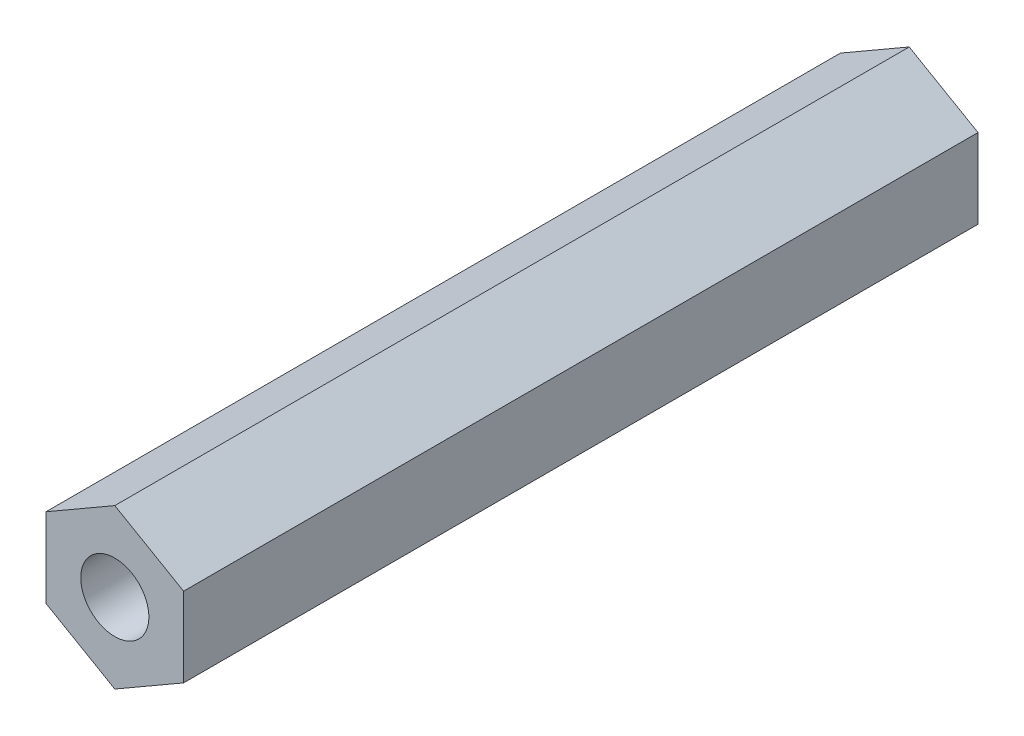
SolidWorks part; units mm, degrees
ref_plane "Front Plane" through (0, 0, 0) normal (0, 0, 1) x (1, 0, 0)
ref_plane "Top Plane" through (0, 0, 0) normal (0, 1, 0) x (1, 0, 0)
ref_plane "Right Plane" through (0, 0, 0) normal (1, 0, 0) x (0, 0, -1)
sketch "Sketch2" plane through (0, 0, 0) normal (0, 0, 1) x (1, 0, 0)
  line L1 (0, -3.5) -> (3.0311, -1.75)
  line L2 (3.0311, -1.75) -> (3.0311, 1.75)
  line L3 (3.0311, 1.75) -> (0, 3.5)
  line L4 (0, 3.5) -> (-3.0311, 1.75)
  line L5 (-3.0311, 1.75) -> (-3.0311, -1.75)
  line L6 (-3.0311, -1.75) -> (0, -3.5)
  circle A0 centre (0, 0) radius 3.0311 construction
  circle A1 centre (0, 0) radius 1.5
  dimension "D1" = 3
  dimension "D2" = 7
  dimension "D3" = 5.25
extrude "Boss-Extrude1" add sketch "Sketch2" along normal blind 35 contours L3 L4 L5 L6 L1 L2
sketch "Sketch3" plane through (0, 0, 0) normal (0, 0, -1) x (-1, 0, 0)
  circle A0 centre (0, 0) radius 1.5
  dimension "D1" = 3
extrude "Cut-Extrude1" cut sketch "Sketch3" against normal blind 35
